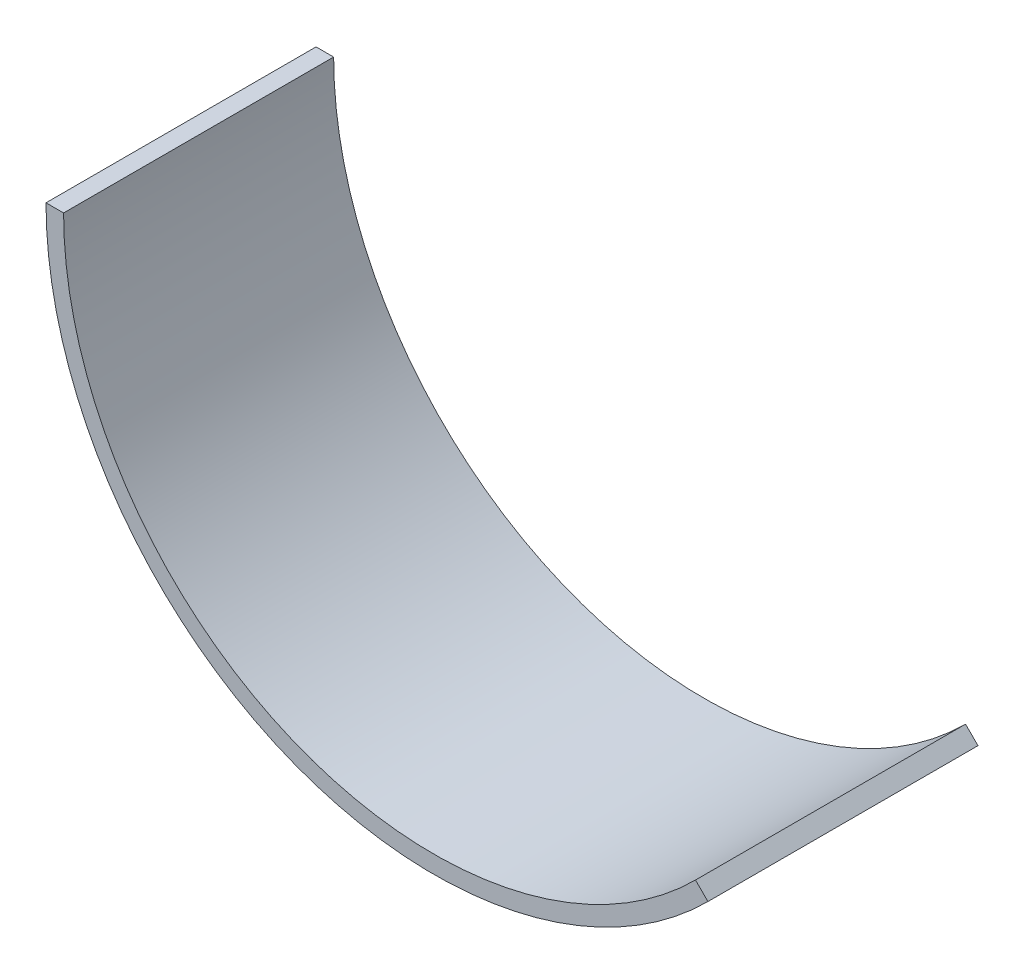
SolidWorks part; units mm, degrees
ref_plane "Front Plane" through (0, 0, 0) normal (0, 0, 1) x (1, 0, 0)
ref_plane "Top Plane" through (0, 0, 0) normal (0, 1, 0) x (1, 0, 0)
ref_plane "Right Plane" through (0, 0, 0) normal (1, 0, 0) x (0, 0, -1)
sketch "Sketch1" plane through (0, 0, 0) normal (0, 0, 1) x (1, 0, 0)
  line L0 (-72.798, 0) -> (-69.496, 0)
  line L1 (49.1411, -49.1411) -> (51.476, -51.476)
  arc A0 (-69.496, 0) -> (49.1411, -49.1411) centre (0, 0) ccw
  arc A1 (-72.798, 0) -> (51.476, -51.476) centre (0, 0) ccw
  dimension "D1" = 69.496
  dimension "D2" = 72.798
extrude "Boss-Extrude1" add sketch "Sketch1" along normal blind 50.7
equation "\"FoamCore\" = \".2\""
equation "\"MDF\" = \".2\""
equation "\"GMaterial\"= \".2\""
equation "\"PVCMountDiameter\" = \"0.5in\""
equation "\"PVCMountDistanceToEdge\" = \"0.5\""
equation "\"PVCThickness\" = \"0.13in\""
equation "\"PVCDiameter\" = 1.5in"
equation "\"BaseWidth\" = \"8in\""
equation "\"BaseLength\" = \"10in\""
equation "\"BallDiameter\" = \"38mm\""
equation "\"BaseGap\" = \"4in\""
equation "\"FunnelTopDiameter\" = \"8in\""
equation "\"FunnelTopDepth\" = \"0.5in\""
equation "\"BallGap\" = \"0.1in\""
equation "\"FunnelLength\" = 3in"
equation "\"FunnelMaterial\" = 0.1in"
equation "\"FunnelLowerDiameter\" = 1.9in"
equation "\"FunnelDepth\" = 1.5in"
equation "\"FunnelBendLength\" = 2*pi*\"FunnelLowerDiameter\"/2*135"
equation "\"AmmoFeederLength\" = 1.5in + 76mm"
equation "\"WheelThickness\" = 0.5in"
equation "\"LauncherWheelDiameter\" = 76mm"
equation "\"MotorFrontLength\" = 0.95in"
equation "\"MotorBodyTotalLength\" = 2.03in"
equation "\"MotorFrontDiameter\" = 1.5in"
equation "\"MotorLowerDriveshaftDiameter\" = 0.46in"
equation "\"MotorLowerDriveshaftThickness\" = 0.25in"
equation "\"MotorFullDriveshaftLength\" = 0.78in"
equation "\"MotorDriveshaftDiameter\" = 0.23in"
equation "\"MotorDriveshaftFlatThickness\" = 0.2in"
equation "\"MotorRearDiameter\" = 31.9mm"
equation "\"MotorDriveshaftBottomToTop\" = 31.1mm"
equation "\"MotorFlatDriveshaftLength\" = 11.7mm"
equation "\"MotorDistanceBetweenLowerandTopHoles\" = 0.5in"
equation "\"MotorMountsDistanceFromEdge\" = 0.06in"
equation "\"MotorScrewMountDiameter\" = 0.1in"
equation "\"MotorScrewMountDepth\" = 0.13in"
equation "\"HBRidgeScrewHoleDeep\" = 0.18in"
equation "\"MotorMountWidth\" = \"1.61in\""
equation "\"MotorMountLength\" = \"1.58in\""
equation "\"MotorMountToEdgeGap\" = \"3.3mm\""
equation "\"MotorMountToInsideEdgeGap\" = \"6.5mm\""
equation "\"MotorMountToMountWidthGap\" = \"25.8mm\""
equation "\"MotorMountToMountLengthGap\" = \"20.5mm\""
equation "\"MotorMountMaterialThickness\" = 1.6mm"
equation "\"MotorMountBaseScrewholeDiameter\" = 3.8mm"
equation "\"MotorMountBaseDistancebetweenHoles\" = 0.8in"
equation "\"MotorMountHeight\" = 1.85in"
equation "\"HBridgeWidth\" = 2.25in"
equation "\"HBridgeLength\" = 1.40in"
equation "\"UnoWidth\" = 3.13in"
equation "\"UnoLength\" = 3.06in"
equation "\"BatteryWidth\" = 1.15in"
equation "\"BatteryLength\" = 3.86in"
equation "\"ScrewDiameter\" = 2.7mm"
equation "\"MotorMountFaceScrewtoBase\" = 0.46in"
equation "\"MotorMountFaceDistanceBetweenScrews\" = 0.95in"
equation "\"MotorMountFaceMiddletoEdge\" = 0.16in"
equation "\"MotorMountFaceBottomtoEdge\" = 0.42in"
equation "\"MotorMountCenterholeHeight\" = 1.04in"
equation "\"MotorMountCenterholetoEdge\" = 0.25in"
equation "\"MovingWheelDiameter\" = 76mm"
equation "\"MovingWheelThickness\" = 0.5in"
equation "\"BraceLength\" = 1in"
equation "\"BraceVerticalOffset\" = 3.5in"
equation "\"BraceHorizontalOffset\" = 2.5in"
equation "\"BaseToBaseDistance\" = 3.6in"
equation "\"PVCOutsideDiameter\" = \"PVCDiameter\" + 2*\"PVCThickness\""
equation "\"Distancebetweenwalls\" = 6in"
equation "\"Slidewidth\" = 0.3in"
equation "\"Slidelength\" = 0.8in"
equation "\"Bottomtofloor\" = 0.53in"
equation "\"tabdistance\" = 0.2in"
equation "\"tabwidth\" = 0.3in"
equation "\"ShooterWheelDiameter\"= 1.88in"
equation "\"ShooterWheelThick\"= 1.03in"
equation "\"ShooterRubberThick\"= 0.3in"
equation "\"3DMaterial\" = \"PVCThickness\""
equation "\"D1@Sketch1\"=(\"ShooterWheelDiameter\"/2) + \"ShooterRubberThick\" + \"BallDiameter\""
equation "\"D2@Sketch1\"=(\"ShooterWheelDiameter\"/2) + \"ShooterRubberThick\" + \"BallDiameter\" + \"3DMaterial\""
equation "\"D1@Boss-Extrude1\"=\"BallDiameter\" +0.1in +(2*\"MDF\")"
